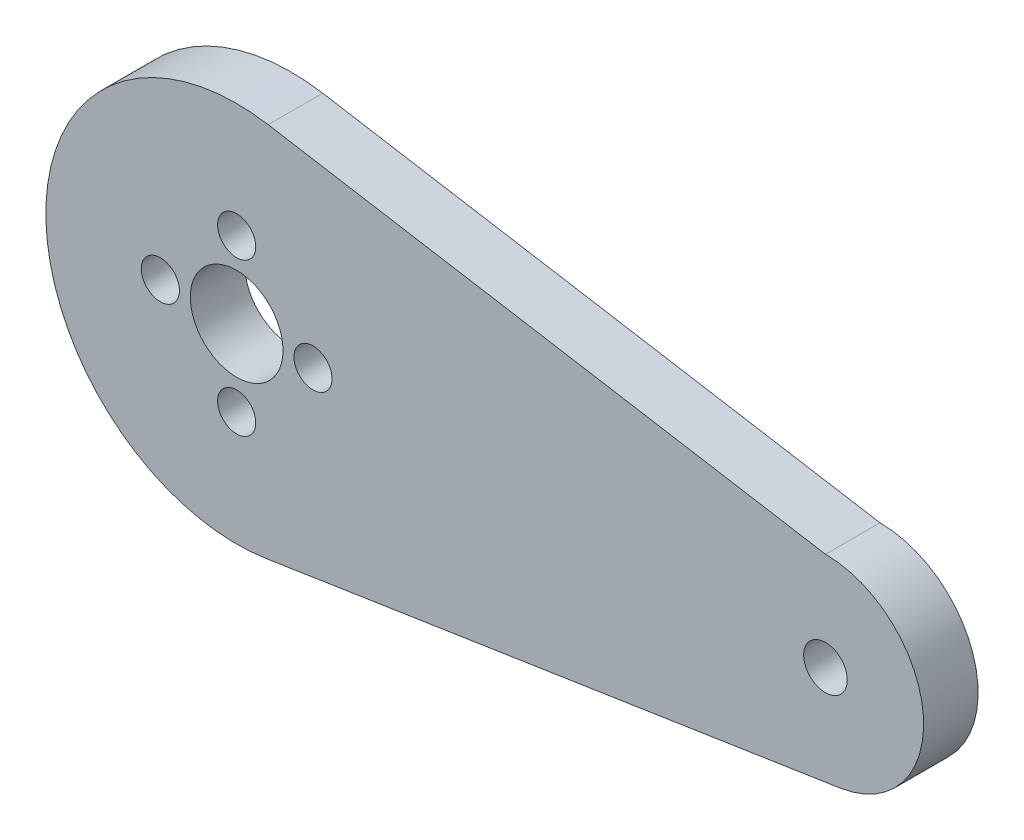
SolidWorks part; units mm, degrees
ref_plane "Front Plane" through (0, 0, 0) normal (0, 0, 1) x (1, 0, 0)
ref_plane "Top Plane" through (0, 0, 0) normal (0, 1, 0) x (1, 0, 0)
ref_plane "Right Plane" through (0, 0, 0) normal (1, 0, 0) x (0, 0, -1)
sketch "Sketch1" plane through (0, 0, 0) normal (0, 0, 1) x (1, 0, 0)
  line L0 (-20.22, 57.58) -> (33.78, 57.2783) construction
  line L1 (-20.22, 57.58) -> (33.78, 57.2783) construction
  circle A0 centre (-20.22, 57.58) radius 17.5 construction
  circle A1 centre (-20.22, 57.58) radius 17.5
sketch "Sketch2" plane through (0, 0, 0) normal (0, 0, 1) x (1, 0, 0)
  line L0 (-17.3289, 74.8395) -> (33.78, 66.2783)
  line L1 (35.147, 48.3828) -> (-17.562, 40.283)
  circle A0 centre (33.78, 57.2783) radius 9 construction
  circle A1 centre (-20.22, 57.58) radius 17.5 construction
  arc A2 (-17.3289, 74.8395) -> (-17.562, 40.283) centre (-20.22, 57.58) ccw
  arc A3 (33.78, 66.2783) -> (35.147, 48.3828) centre (33.78, 57.2783) cw
  circle A4 centre (-20.22, 57.58) radius 4.25
  circle A5 centre (33.78, 57.2783) radius 2
  dimension "D1" = 18
  dimension "D2" = 4
  dimension "D3" = 8.5
extrude "Boss-Extrude1" add sketch "Sketch2" against normal blind 5
sketch "草图1" plane through (0, 0, 0) normal (0, 0, 1) x (1, 0, 0)
  line L0 (-20.22, 50.58) -> (-20.22, 64.58) construction
  line L1 (-13.22, 57.58) -> (-27.22, 57.58) construction
  circle A0 centre (-13.22, 57.58) radius 1.75
  circle A1 centre (-27.22, 57.58) radius 1.75
  circle A2 centre (-20.22, 64.58) radius 1.75
  circle A3 centre (-20.22, 50.58) radius 1.75
  circle A5 centre (-20.22, 57.58) radius 4.25 construction
  point P10 (-20.22, 57.58)
  point P11 (-20.22, 57.58)
  dimension "D1" = 3.5
  dimension "D2" = 14
  dimension "D3" = 14
extrude "切除-拉伸1" cut sketch "草图1" against normal blind 10
